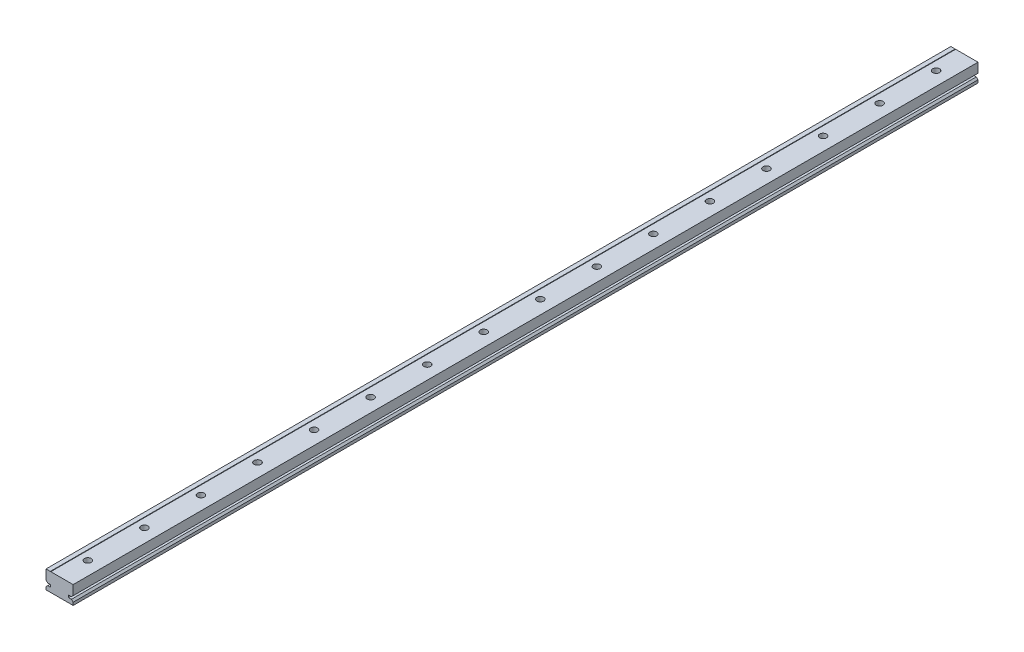
SolidWorks part; units mm, degrees
ref_plane "Front Plane" through (0, 0, 0) normal (0, 0, 1) x (1, 0, 0)
ref_plane "Top Plane" through (0, 0, 0) normal (0, 1, 0) x (1, 0, 0)
ref_plane "Right Plane" through (0, 0, 0) normal (1, 0, 0) x (0, 0, -1)
sketch "Sketch1" plane through (0, 0, 0) normal (0, 0, 1) x (1, 0, 0)
  line L0 (-6, -2.75) -> (-6, -4)
  line L1 (-6, 4) -> (-4.1118, 4)
  line L2 (-6, 4) -> (-6, -0.25)
  line L3 (-6, -4) -> (6, -4)
  line L4 (6, 4) -> (6, -0.25)
  line L5 (-6, 4) -> (6, -4) construction
  line L6 (-6, -4) -> (6, 4) construction
  line L7 (-5.25, -2) -> (-4, -2)
  line L9 (-5.25, -1) -> (-4, -1)
  line L10 (-4, -2) -> (-4, -1)
  line L11 (-5.25, -1) -> (-6, -0.25)
  line L12 (-5.25, -2) -> (-6, -2.75)
  line L13 (0, 0) -> (0, -5.6806) construction
  line L14 (5.25, -2) -> (6, -2.75)
  line L15 (5.25, -2) -> (4, -2)
  line L16 (4, -2) -> (4, -1)
  line L17 (5.25, -1) -> (4, -1)
  line L18 (5.25, -1) -> (6, -0.25)
  line L19 (6, -2.75) -> (6, -4)
  line L20 (-4, 3.9) -> (-4.1118, 4)
  line L22 (-3.8882, 4) -> (-4, 3.9)
  line L23 (-4, -1) -> (-4, 4) construction
  line L24 (-3.8882, 4) -> (6, 4)
  point P0 (0, 0)
  point P6 (-4.625, -2)
  point P23 (-3.4518, 4)
  point P26 (-3.9196, 4)
  point P27 (0, 0)
  dimension "D1" = 8
  dimension "D2" = 12
  dimension "D3" = 2
  dimension "D4" = 1
  dimension "D5" = 0.1
  dimension "D6" = 0.15
  dimension "D7" = 0.15
extrude "Boss-Extrude1" add sketch "Sketch1" along normal blind 400
sketch "Sketch2" plane through (0, -4, 0) normal (0, -1, 0) x (1, 0, 0)
  circle A0 centre (0, 12.5) radius 1.5
extrude "Cut-Extrude1" cut sketch "Sketch2" against normal blind 10
pattern_linear "LPattern1" count 16 spacing 25 along (0, 0, 1) of "Cut-Extrude1"
